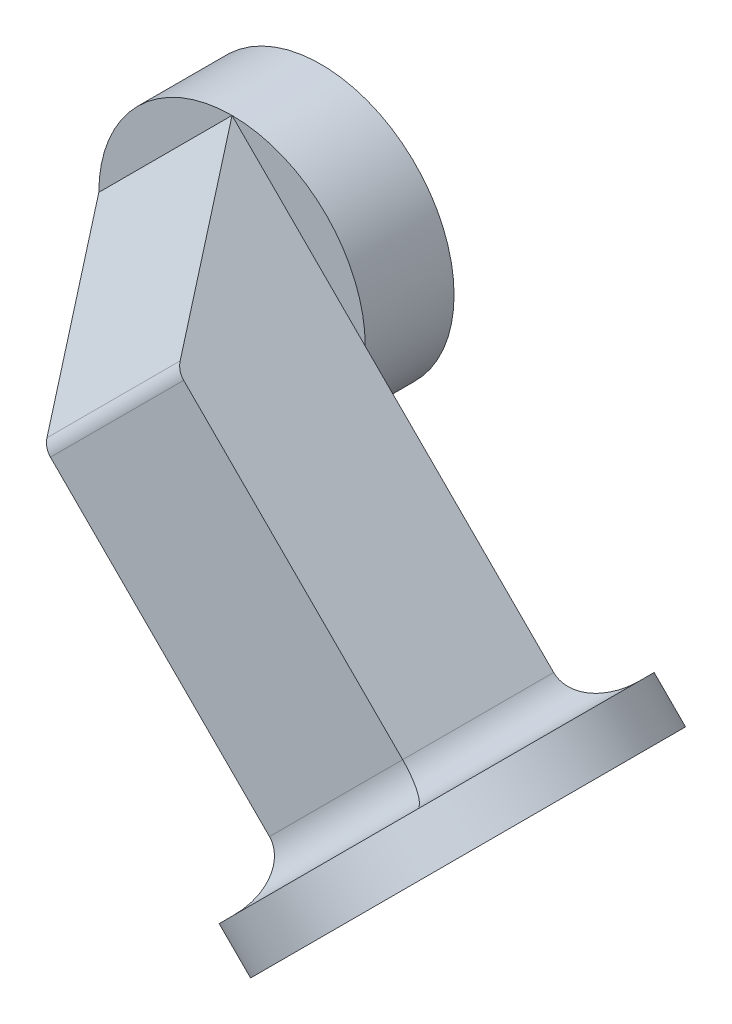
SolidWorks part; units mm, degrees
ref_plane "Front Plane" through (0, 0, 0) normal (0, 0, 1) x (1, 0, 0)
ref_plane "Top Plane" through (0, 0, 0) normal (0, 1, 0) x (1, 0, 0)
ref_plane "Right Plane" through (0, 0, 0) normal (1, 0, 0) x (0, 0, -1)
sketch "Sketch1" plane through (0, 0, 0) normal (0, 0, 1) x (1, 0, 0)
  circle A0 centre (0, 0) radius 19.05
extrude "Boss-Extrude1" add sketch "Sketch1" along normal blind 12.7
sketch "Sketch2" plane through (0, 0, 12.7) normal (0, 0, 1) x (1, 0, 0)
  line L0 (-19.05, 0) -> (0, -19.05)
  line L1 (0, -19.05) -> (19.05, 0)
  line L2 (19.05, 0) -> (0, 19.05)
  line L3 (0, 19.05) -> (-19.05, 0)
  circle A0 centre (0, 0) radius 19.05 construction
  point P1 (19.05, 0)
  point P4 (0, 19.05)
  point P5 (-19.05, 0)
  point P6 (0, -19.05)
extrude "Boss-Extrude2" add sketch "Sketch2" along normal blind 21.59
sketch "Sketch4" plane through (9.525, -9.525, 0) normal (0.7071, -0.7071, 0) x (0, 0, -1)
  line L0 (-34.29, -13.4704) -> (-12.7, -13.4704) construction
  line L1 (-12.7, -13.4704) -> (-12.7, 13.4704) construction
  line L2 (-34.29, -13.4704) -> (-34.29, 13.4704) construction
  line L3 (-34.29, 13.4704) -> (-12.7, 13.4704) construction
  line L4 (-34.29, -13.4704) -> (-12.7, -13.4704)
  line L5 (-12.7, -13.4704) -> (-12.7, 13.4704)
  line L6 (-34.29, -13.4704) -> (-34.29, 13.4704)
  line L7 (-34.29, 13.4704) -> (-12.7, 13.4704)
extrude "Boss-Extrude3" add sketch "Sketch4" along normal blind 43.18
sketch "Sketch5" plane through (9.525, 9.525, 0) normal (0.7071, 0.7071, 0) x (0, 0, -1)
  line L0 (-34.29, -56.6504) -> (-34.29, 13.4704) construction
  line L1 (-34.29, -6.1559) -> (-12.7, 13.4704)
  line L2 (-12.7, 13.4704) -> (-34.29, 13.4704)
  line L3 (-34.29, 13.4704) -> (-34.29, -6.1559)
  point P0 (-12.7, 13.4704)
  point P1 (-34.29, -6.1559)
  point P3 (-34.29, 13.4704)
extrude "Cut-Extrude1" cut sketch "Sketch5" against normal blind 43.18
fillet "Fillet2" radius 2.54 1 edges at (4.3529, -4.3529, 34.29)
sketch "Sketch6" plane through (40.0579, -40.0579, 0) normal (0.7071, -0.7071, 0) x (0, 0, -1)
  line L0 (-34.29, 13.4704) -> (-12.7, -13.4704) construction
  line L1 (-12.7, 13.4704) -> (-34.29, -13.4704) construction
  circle A0 centre (-23.495, 0) radius 25.4
extrude "Boss-Extrude4" add sketch "Sketch6" along normal blind 6.35
fillet "Fillet5" radius 5.08 4 edges at (40.0579, -40.0579, 34.29) (30.5329, -49.5829, 23.495) (40.0579, -40.0579, 12.7) (49.5829, -30.5329, 23.495)
sketch "Sketch7" plane through (0, 0, 0) normal (0, 0, -1) x (-1, 0, 0)
  circle A0 centre (0, 0) radius 4.064
extrude "Cut-Extrude2" cut sketch "Sketch7" against normal blind 2.032
